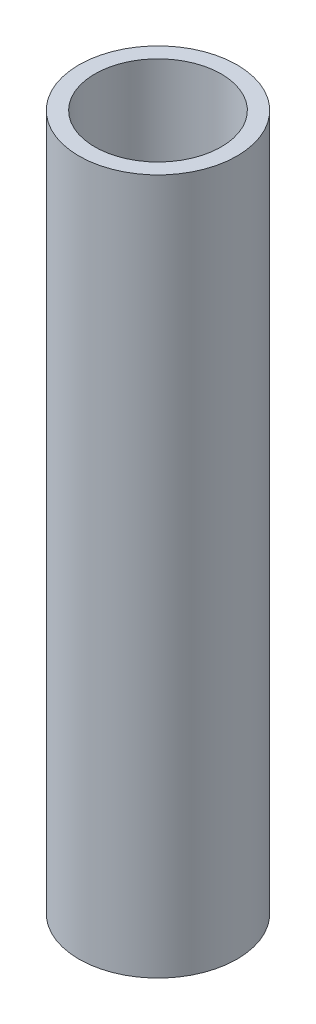
SolidWorks part; units mm, degrees
ref_plane "Płaszczyzna przednia" through (0, 0, 0) normal (0, 0, 1) x (1, 0, 0)
ref_plane "Płaszczyzna górna" through (0, 0, 0) normal (0, 1, 0) x (1, 0, 0)
ref_plane "Płaszczyzna prawa" through (0, 0, 0) normal (1, 0, 0) x (0, 0, -1)
sketch "Sketch1" plane through (0, 0, 0) normal (0, 0, 1) x (1, 0, 0)
  line L0 (0, 0) -> (0, 66) construction
  line L1 (6, 66) -> (0, 66) construction
  line L2 (6, 0) -> (7.5, 0)
  line L3 (6, 0) -> (6, 66)
  line L4 (6, 66) -> (7.5, 66)
  line L5 (7.5, 0) -> (7.5, 66)
  dimension "D1" = 6
  dimension "D2" = 1.5
  dimension "D3" = 66
revolve "Revolve1" add sketch "Sketch1" angle 360 about L0
